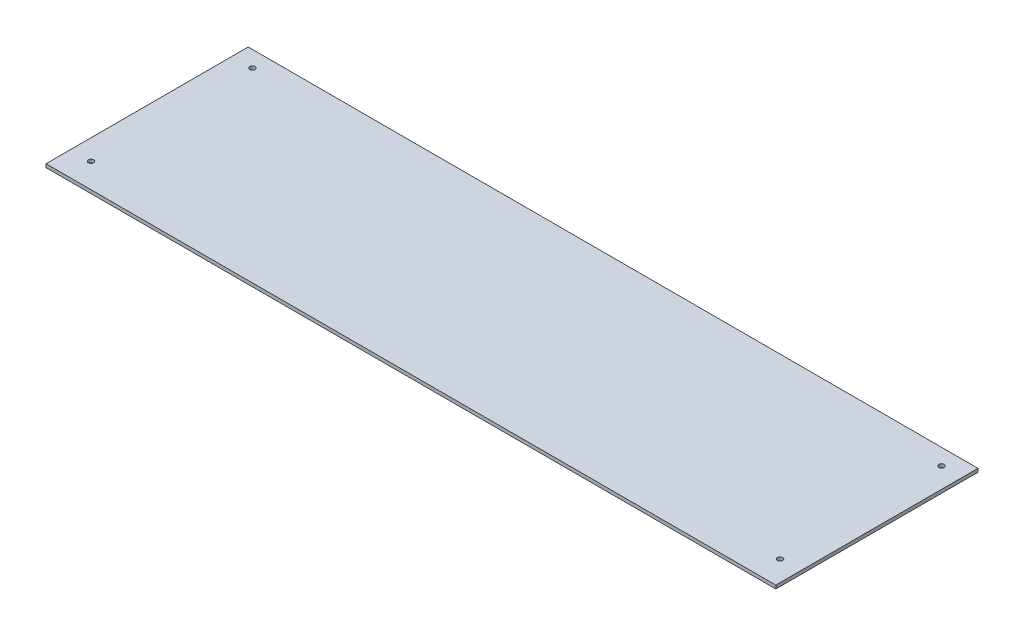
SolidWorks part; units mm, degrees
ref_plane "Alzado" through (0, 0, 0) normal (0, 0, 1) x (1, 0, 0)
ref_plane "Planta" through (0, 0, 0) normal (0, 1, 0) x (1, 0, 0)
ref_plane "Vista lateral" through (0, 0, 0) normal (1, 0, 0) x (0, 0, -1)
sketch "Croquis1" plane through (0, 0, 0) normal (0, 1, 0) x (1, 0, 0)
  line L0 (215.25, 120) -> (215.25, 0) construction
  line L1 (0, 0) -> (430.5, 0)
  line L2 (0, 0) -> (0, 120)
  line L3 (0, 120) -> (430.5, 120)
  line L4 (430.5, 0) -> (430.5, 120)
  line L5 (0, 60) -> (430.5, 60) construction
  circle A0 centre (12.5, 15) radius 1.55
  circle A1 centre (12.5, 110) radius 1.55
  circle A2 centre (418, 15) radius 1.55
  circle A3 centre (418, 110) radius 1.55
  dimension "D3" = 3.1
  dimension "D1" = 120
  dimension "D2" = 430.5
  dimension "D4" = 15
  dimension "D5" = 12.5
  dimension "D6" = 12.5
  dimension "D7" = 10
extrude "Saliente-Extruir1" add sketch "Croquis1" along normal blind 2
sketch "Croquis2" plane through (0, 0, 0) normal (0, -1, 0) x (1, 0, 0)
  line L0 (430, -0.5) -> (0.5, -0.5)
  line L1 (0.5, -0.5) -> (0.5, -119.5)
  line L2 (0.5, -119.5) -> (430, -119.5)
  line L3 (430, -119.5) -> (430, -0.5)
  line L4 (0, 0) -> (0, -120)
  line L5 (0, -120) -> (430.5, -120)
  line L6 (430.5, -120) -> (430.5, 0)
  line L7 (430.5, 0) -> (0, 0)
  line L8 (0, 0) -> (0, -120)
  line L9 (0, -120) -> (430.5, -120)
  line L10 (430.5, -120) -> (430.5, 0)
  line L11 (430.5, 0) -> (0, 0)
  dimension "D1" = 0
  dimension "D2" = 0.5
extrude "Cortar-Extruir1" cut sketch "Croquis2" against normal up to surface (2 mm away) up to face at (215.25, 2, -60)
